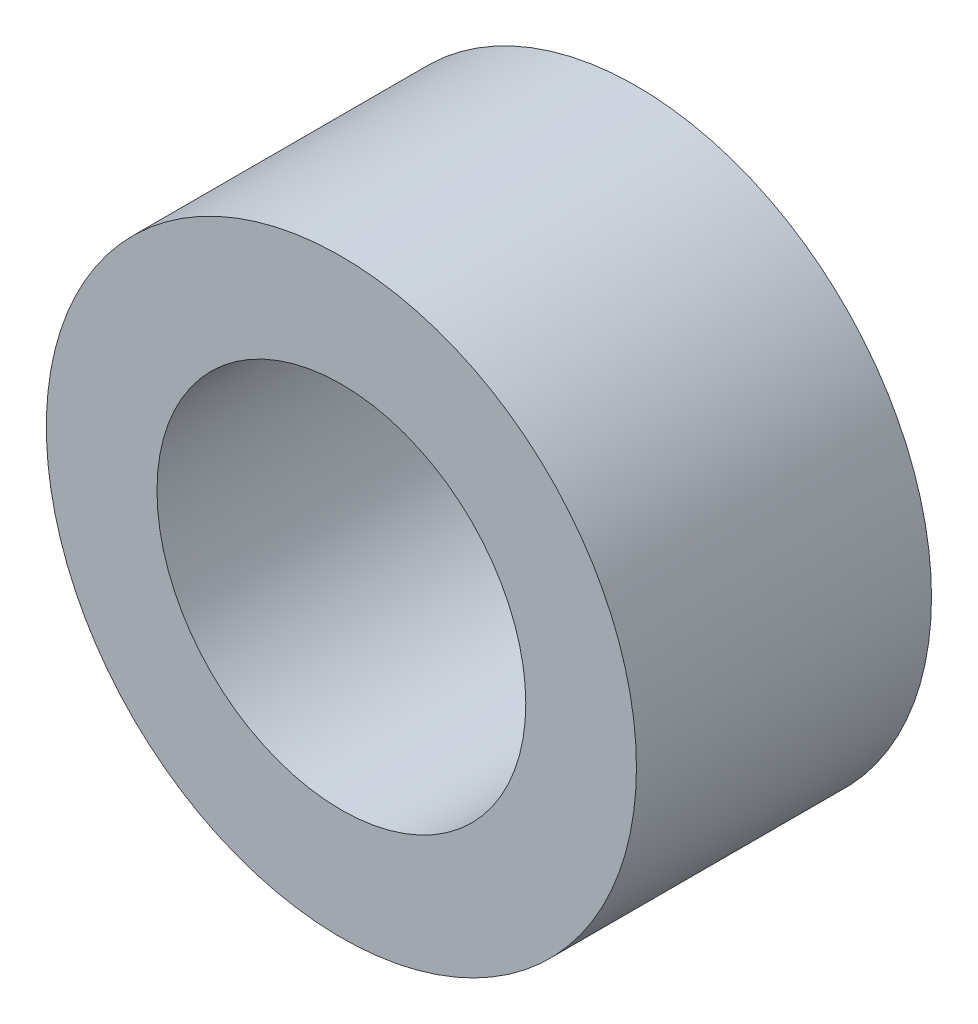
SolidWorks part; units mm, degrees
ref_plane "Front Plane" through (0, 0, 0) normal (0, 0, 1) x (1, 0, 0)
ref_plane "Top Plane" through (0, 0, 0) normal (0, 1, 0) x (1, 0, 0)
ref_plane "Right Plane" through (0, 0, 0) normal (1, 0, 0) x (0, 0, -1)
sketch "Sketch1" plane through (0, 0, 0) normal (0, 0, 1) x (1, 0, 0)
  circle A0 centre (0, 0) radius 3.125
  circle A1 centre (0, 0) radius 5
  dimension "D1" = 6.25
  dimension "D2" = 10
extrude "Boss-Extrude1" add sketch "Sketch1" along normal blind 5
